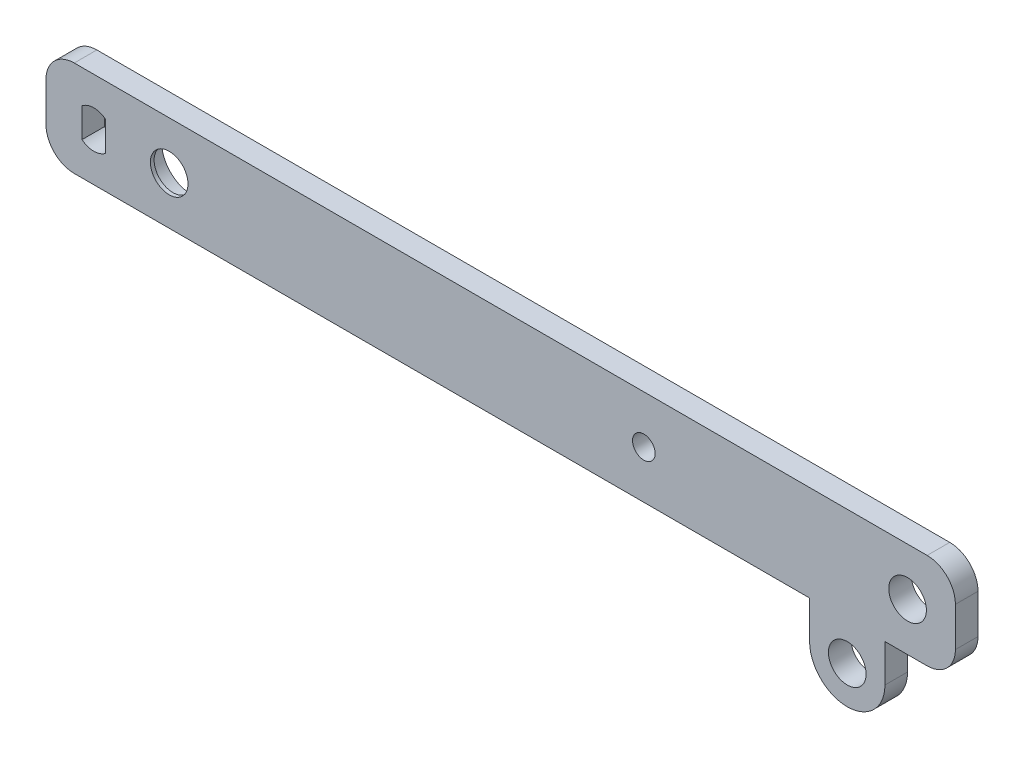
SolidWorks part; units mm, degrees
ref_plane "Alzado" through (0, 0, 0) normal (0, 0, 1) x (1, 0, 0)
ref_plane "Planta" through (0, 0, 0) normal (0, 1, 0) x (1, 0, 0)
ref_plane "Vista lateral" through (0, 0, 0) normal (1, 0, 0) x (0, 0, -1)
sketch "Croquis1" plane through (0, 0, 0) normal (0, 0, 1) x (1, 0, 0)
  line L0 (0, 0) -> (432, 0) construction
  line L1 (380, -45.4) -> (380, -25.4)
  line L2 (-6.28, -7.7821) -> (-6.28, 7.7821)
  line L3 (-25.4, 25.4) -> (457.4, 25.4)
  line L4 (6.28, -7.7821) -> (6.28, 7.7821)
  line L5 (-6.28, -7.7821) -> (6.28, 7.7821) construction
  line L6 (-6.28, 7.7821) -> (6.28, -7.7821) construction
  line L7 (-25.4, 25.4) -> (-25.4, -25.4)
  line L8 (-25.4, -25.4) -> (380, -25.4)
  line L9 (457.4, 25.4) -> (457.4, -25.4)
  line L10 (420, -45.4) -> (420, -25.4)
  line L11 (420, -25.4) -> (457.4, -25.4)
  arc A0 (-6.28, -7.7821) -> (6.28, -7.7821) centre (0, 0) ccw
  arc A1 (6.28, 7.7821) -> (-6.28, 7.7821) centre (0, 0) ccw
  circle A2 centre (432, 0) radius 10
  circle A3 centre (40, 0) radius 10
  circle A4 centre (292, 0) radius 6
  circle A5 centre (400, -45.4) radius 10
  arc A6 (380, -45.4) -> (420, -45.4) centre (400, -45.4) ccw
  dimension "D1" = 20
  dimension "D4" = 20
  dimension "D5" = 20
  dimension "D6" = 40
  dimension "D9" = 25.4
  dimension "D10" = 25.4
  dimension "D11" = 12
  dimension "D12" = 140
  dimension "D13" = 20
  dimension "D14" = 20
  dimension "D15" = 20
  dimension "D16" = 360
  dimension "D2" = 12.56
  dimension "D3" = 432
  dimension "D7" = 50.8
  dimension "D8" = 25.4
extrude "Saliente-Extruir1" add sketch "Croquis1" along normal blind 12
sketch "Croquis2" plane through (0, 0, 0) normal (0, 0, -1) x (-1, 0, 0)
  circle A0 centre (-66.437, -11.2982) radius 2.145
extrude "Cortar-Extruir1" cut sketch "Croquis2" against normal blind 3
sketch "Croquis3" plane through (0, 0, 0) normal (0, 0, -1) x (-1, 0, 0)
  circle A0 centre (-40, 0) radius 16
  dimension "D1" = 32
extrude "Cortar-Extruir2" cut sketch "Croquis3" against normal blind 10
fillet "Redondeo1" radius 15 2 edges at (-25.4, -25.4, 6) (-25.4, 25.4, 6)
fillet "Redondeo2" radius 15 2 edges at (457.4, -25.4, 6) (457.4, 25.4, 6)
